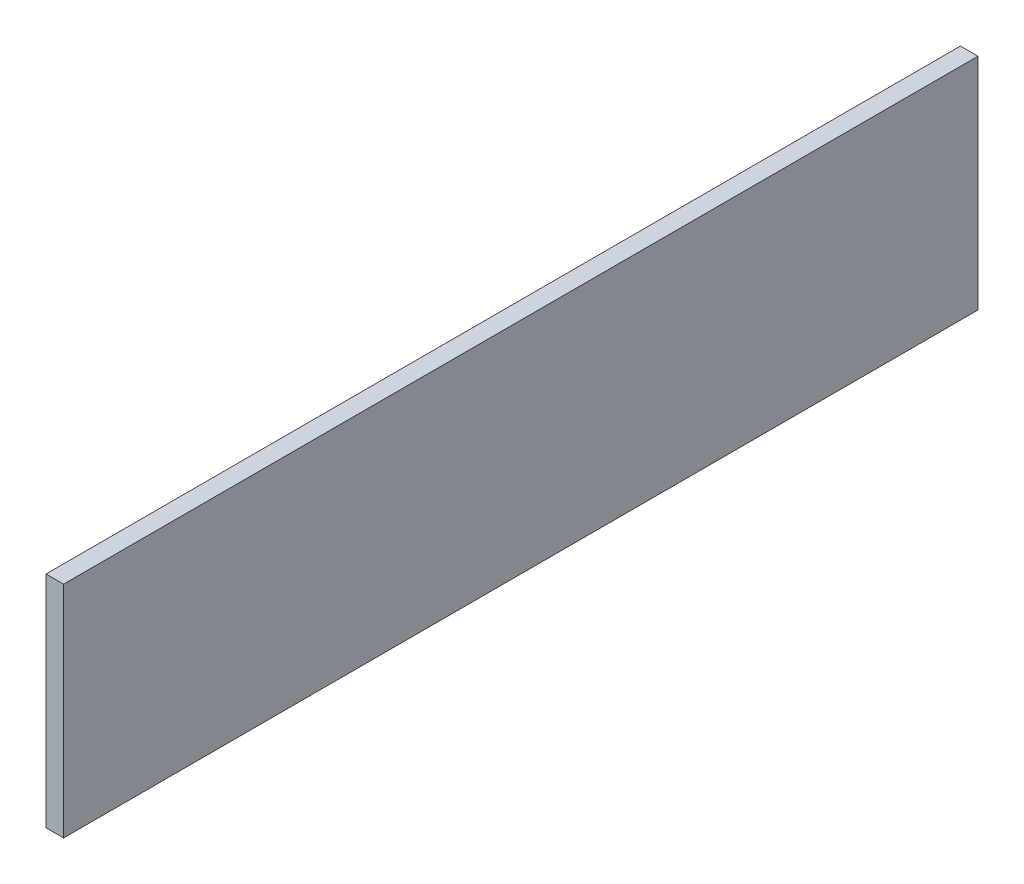
SolidWorks part; units mm, degrees
ref_plane "Front Plane" through (0, 0, 0) normal (0, 0, 1) x (1, 0, 0)
ref_plane "Top Plane" through (0, 0, 0) normal (0, 1, 0) x (1, 0, 0)
ref_plane "Right Plane" through (0, 0, 0) normal (1, 0, 0) x (0, 0, -1)
sketch "Sketch2" plane through (0, 0, 0) normal (0, 1, 0) x (1, 0, 0)
  line L1 (80, -4160) -> (-80, -4160)
  line L2 (80, -4160) -> (80, 4160)
  line L3 (80, 4160) -> (-80, 4160)
  line L4 (-80, -4160) -> (-80, 4160)
  line L5 (80, -4160) -> (-80, 4160) construction
  line L6 (80, 4160) -> (-80, -4160) construction
  point P0 (0, 0)
  point P8 (-102.6971, 4243.2104)
  dimension "D1" = 8320
  dimension "D2" = 160
extrude "Boss-Extrude1" add sketch "Sketch2" along normal blind 2000
